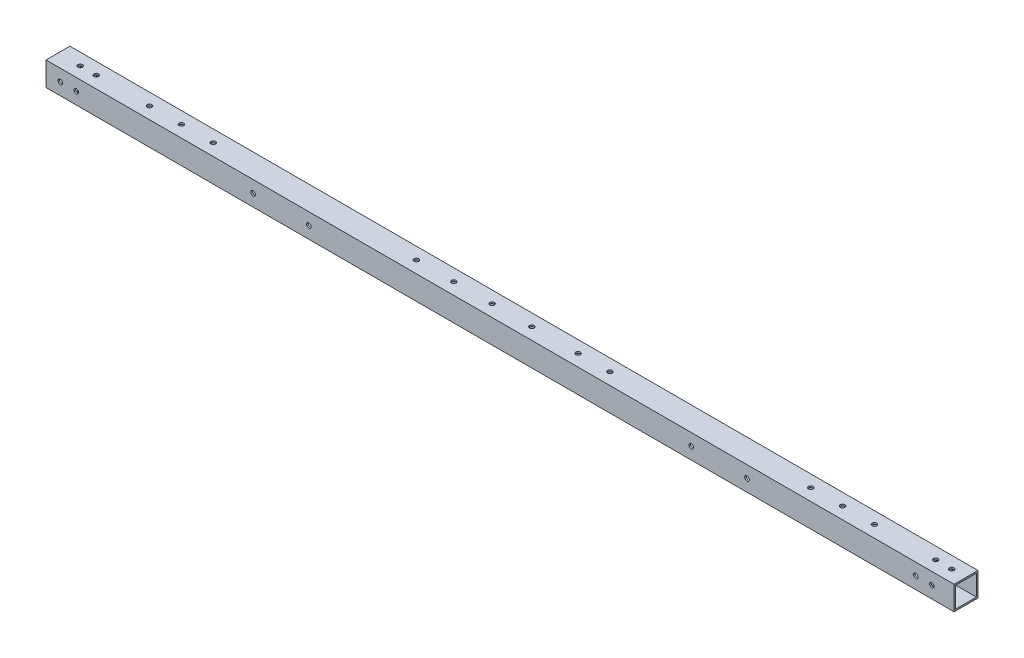
SolidWorks part; units mm, degrees
material "Thornel Mat VMA"
ref_plane "前视基准面" through (0, 0, 0) normal (0, 0, 1) x (1, 0, 0)
ref_plane "上视基准面" through (0, 0, 0) normal (0, 1, 0) x (1, 0, 0)
ref_plane "右视基准面" through (0, 0, 0) normal (1, 0, 0) x (0, 0, -1)
other "Configuration Table"
sketch "草图1" plane through (0, 0, 0) normal (1, 0, 0) x (0, 0, -1)
  line L0 (-6.5, -6.5) -> (-6.5, 6.5)
  line L1 (-7.5, -7.5) -> (7.5, -7.5)
  line L2 (-7.5, -7.5) -> (-7.5, 7.5)
  line L3 (-7.5, 7.5) -> (7.5, 7.5)
  line L4 (7.5, -7.5) -> (7.5, 7.5)
  line L5 (-7.5, -7.5) -> (7.5, 7.5) construction
  line L6 (-7.5, 7.5) -> (7.5, -7.5) construction
  line L7 (-6.5, 6.5) -> (6.5, 6.5)
  line L8 (6.5, -6.5) -> (6.5, 6.5)
  line L9 (-6.5, -6.5) -> (6.5, -6.5)
  point P0 (0, 0)
  dimension "D1" = 15
  dimension "D2" = 15
  dimension "D3" = 1
extrude "凸台-拉伸1" add sketch "草图1" along normal blind 570
sketch "草图2" plane through (0, 7.5, 0) normal (0, 1, 0) x (1, 0, 0)
  circle A0 centre (561, 0) radius 1.45 construction
  circle A1 centre (551, 0) radius 1.45 construction
  circle A2 centre (297.5, 0) radius 1.45 construction
  circle A3 centre (272.5, 0) radius 1.45 construction
  circle A4 centre (24, 0) radius 1.45 construction
  circle A5 centre (14, 0) radius 1.45 construction
  circle A6 centre (561, 0) radius 1.45
  circle A7 centre (551, 0) radius 1.45
  circle A8 centre (297.5, 0) radius 1.45
  circle A9 centre (272.5, 0) radius 1.45
  circle A10 centre (24, 0) radius 1.45
  circle A11 centre (14, 0) radius 1.45
  circle A12 centre (97.5, 0) radius 1.45 construction
  circle A13 centre (77.5, 0) radius 1.45 construction
  circle A14 centre (57.5, 0) radius 1.45 construction
  circle A15 centre (472.5, 0) radius 1.45 construction
  circle A16 centre (492.5, 0) radius 1.45 construction
  circle A17 centre (512.5, 0) radius 1.45 construction
  circle A18 centre (97.5, 0) radius 1.45
  circle A19 centre (77.5, 0) radius 1.45
  circle A20 centre (57.5, 0) radius 1.45
  circle A21 centre (472.5, 0) radius 1.45
  circle A22 centre (492.5, 0) radius 1.45
  circle A23 centre (512.5, 0) radius 1.45
  circle A24 centre (346.5, 0) radius 1.45 construction
  circle A25 centre (326.5, 0) radius 1.45 construction
  circle A26 centre (248.5, 0) radius 1.45 construction
  circle A27 centre (225, 0) radius 1.45 construction
  circle A28 centre (346.5, 0) radius 1.45
  circle A29 centre (326.5, 0) radius 1.45
  circle A30 centre (248.5, 0) radius 1.45
  circle A31 centre (225, 0) radius 1.45
extrude "切除-拉伸1" cut sketch "草图2" against normal through all
sketch "草图3" plane through (0, 0, 7.5) normal (0, 0, 1) x (1, 0, 0)
  circle A2 centre (440, 0) radius 1.45 construction
  circle A3 centre (405, 0) radius 1.45 construction
  circle A4 centre (165, 0) radius 1.45 construction
  circle A5 centre (130, 0) radius 1.45 construction
  circle A6 centre (19, 0) radius 1.45 construction
  circle A7 centre (9, 0) radius 1.45 construction
  circle A10 centre (440, 0) radius 1.45
  circle A11 centre (405, 0) radius 1.45
  circle A12 centre (165, 0) radius 1.45
  circle A13 centre (130, 0) radius 1.45
  circle A14 centre (19, 0) radius 1.45
  circle A15 centre (9, 0) radius 1.45
  circle A16 centre (556, 0) radius 1.45 construction
  circle A17 centre (546, 0) radius 1.45 construction
  circle A18 centre (556, 0) radius 1.45
  circle A19 centre (546, 0) radius 1.45
extrude "切除-拉伸2" cut sketch "草图3" against normal through all
